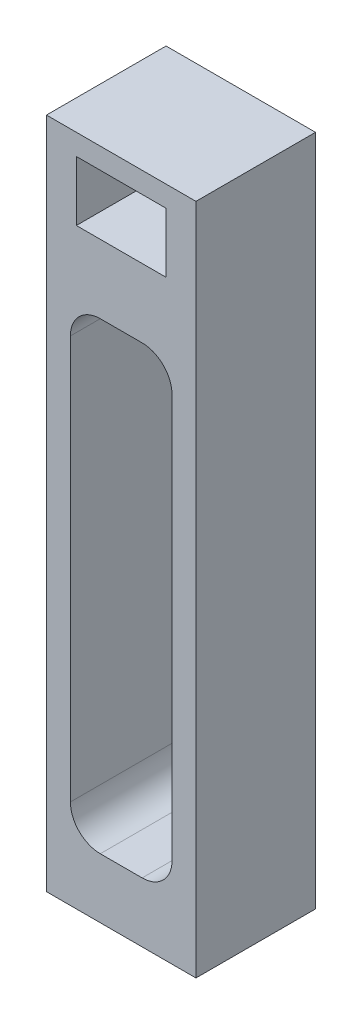
SolidWorks part; units mm, degrees
ref_plane "Front Plane" through (0, 0, 0) normal (0, 0, 1) x (1, 0, 0)
ref_plane "Top Plane" through (0, 0, 0) normal (0, 1, 0) x (1, 0, 0)
ref_plane "Right Plane" through (0, 0, 0) normal (1, 0, 0) x (0, 0, -1)
sketch "Sketch1" plane through (0, 0, 0) normal (0, 1, 0) x (1, 0, 0)
  line L1 (-12.5, -10) -> (12.5, -10)
  line L2 (-12.5, -10) -> (-12.5, 10)
  line L3 (-12.5, 10) -> (12.5, 10)
  line L4 (12.5, -10) -> (12.5, 10)
  line L5 (-12.5, -10) -> (12.5, 10) construction
  line L6 (-12.5, 10) -> (12.5, -10) construction
  point P0 (0, 0)
  dimension "D1" = 20
  dimension "D2" = 25
extrude "Boss-Extrude1" add sketch "Sketch1" along normal blind 100 and the other way blind 12.5
sketch "Sketch2" plane through (0, 0, 10) normal (0, 0, 1) x (1, 0, 0)
  line L0 (-12.5, 100) -> (12.5, 100) construction
  line L1 (-7.5, 86.5) -> (7.5, 86.5)
  line L2 (-7.5, 86.5) -> (-7.5, 96.5)
  line L3 (-7.5, 96.5) -> (7.5, 96.5)
  line L4 (7.5, 86.5) -> (7.5, 96.5)
  line L5 (-7.5, 86.5) -> (7.5, 96.5) construction
  line L6 (-7.5, 96.5) -> (7.5, 86.5) construction
  line L7 (12.5, -12.5) -> (12.5, 100) construction
  line L8 (-12.5, -12.5) -> (-12.5, 100) construction
  point P0 (0, 91.5)
  point P7 (0, 100)
  dimension "D1" = 3.5
  dimension "D2" = 5
  dimension "D3" = 5
  dimension "D4" = 10
extrude "Cut-Extrude1" cut sketch "Sketch2" against normal through all
sketch "Sketch3" plane through (0, 0, 10) normal (0, 0, 1) x (1, 0, 0)
  line L0 (-12.5, -12.5) -> (-12.5, 100) construction
  line L1 (-3.5, -2.5) -> (3.5, -2.5)
  line L2 (-8.5, 2.5) -> (-8.5, 70)
  line L3 (-3.5, 75) -> (3.5, 75)
  line L4 (8.5, 2.5) -> (8.5, 70)
  line L5 (12.5, -12.5) -> (12.5, 100) construction
  line L6 (-12.5, -12.5) -> (12.5, -12.5) construction
  line L7 (-12.5, 100) -> (12.5, 100) construction
  arc A0 (-8.5, 2.5) -> (-3.5, -2.5) centre (-3.5, 2.5) ccw
  arc A1 (3.5, -2.5) -> (8.5, 2.5) centre (3.5, 2.5) ccw
  arc A2 (8.5, 70) -> (3.5, 75) centre (3.5, 70) ccw
  arc A3 (-3.5, 75) -> (-8.5, 70) centre (-3.5, 70) ccw
  point P10 (0, -12.5)
  dimension "D5" = 5
  dimension "D1" = 4
  dimension "D2" = 4
  dimension "D3" = 10
  dimension "D4" = 25
extrude "Cut-Extrude2" cut sketch "Sketch3" against normal through all
